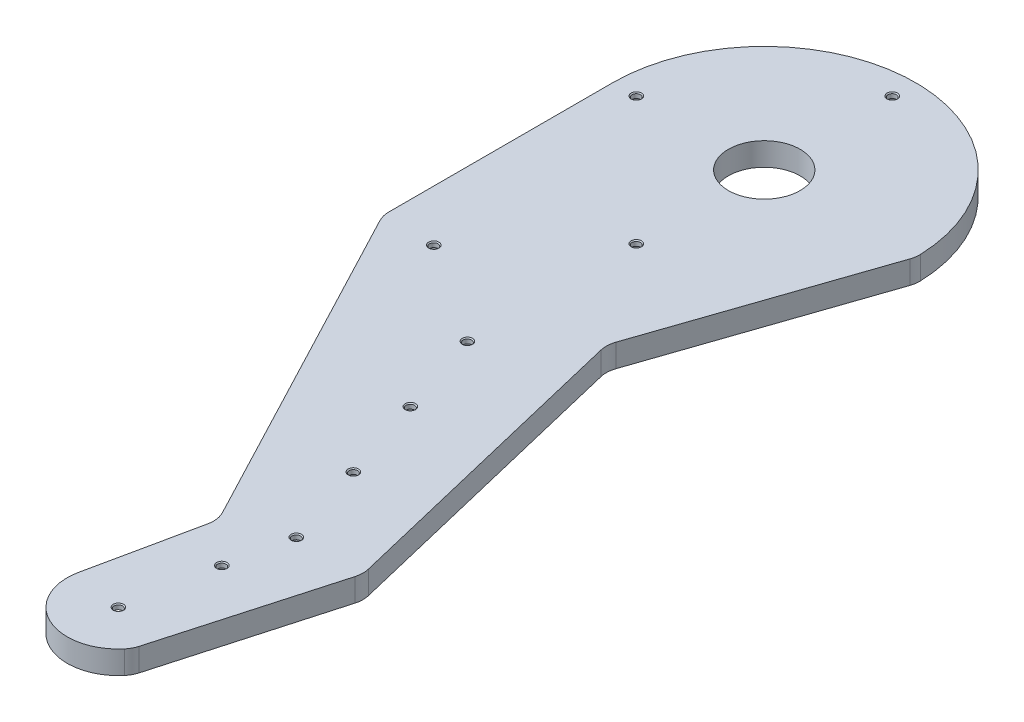
SolidWorks part; units mm, degrees
ref_plane "前视基准面" through (0, 0, 0) normal (0, 0, 1) x (1, 0, 0)
ref_plane "上视基准面" through (0, 0, 0) normal (0, 1, 0) x (1, 0, 0)
ref_plane "右视基准面" through (0, 0, 0) normal (1, 0, 0) x (0, 0, -1)
sketch "草图1" plane through (0, 0, 0) normal (0, 1, 0) x (1, 0, 0)
  line L1 (59.1175, 105.8237) -> (28.3621, 15.8237)
  line L2 (28.3621, 15.8237) -> (58.3577, -109.1763)
  line L3 (58.3577, -109.1763) -> (38.6011, -179.1763)
  line L4 (-59.1082, 15.8237) -> (11.7869, -119.1763)
  line L5 (-59.1175, 105.8237) -> (-59.1082, 15.8237)
  line L6 (11.7869, -119.1763) -> (2.2339, -164.1763)
  arc A0 (59.1175, 105.8237) -> (-59.1175, 105.8115) centre (0, 105.8237) ccw
  arc A1 (2.2339, -164.1763) -> (38.6011, -179.1763) centre (21.7979, -168.3296) ccw
  point P3 (0, 105.8237)
  dimension "D4" = 70
  dimension "D8" = 20
  dimension "D1" = 90
  dimension "D3" = 125
  dimension "D5" = 135
  dimension "D6" = 45
  dimension "D7" = 90
extrude "凸台-拉伸1" add sketch "草图1" along normal blind 5 contours L6 A1 L3 L2 L1 A0 L5 L4
sketch "草图5" plane through (0, 0, 0) normal (0, -1, 0) x (-1, 0, 0)
  circle A1 centre (-21.7979, -168.3296) radius 14
sketch "草图6" plane through (0, 5, 0) normal (0, 1, 0) x (1, 0, 0)
  circle A1 centre (0, 155.8237) radius 5
  circle A2 centre (0, 55.8237) radius 5
  circle A3 centre (-50, 105.8237) radius 5
  circle A4 centre (-39.1082, 15.8237) radius 5
  circle A5 centre (50, 105.8237) radius 5 [skipped]
  point P0 (0, 0)
  point P5 (0, 105.8237)
  dimension "D1" = 4
  dimension "D2" = 50
  dimension "D3" = 50
  dimension "D4" = 50
  dimension "D5" = 50
fillet "圆角1" radius 10 6 edges at (59.1175, 2.5, -105.8237) (38.6011, 2.5, 179.1763) (11.7869, 2.5, 119.1763) (58.3577, 2.5, 109.1763) (28.3621, 2.5, -15.8237) (-59.1082, 2.5, -15.8237)
sketch "草图7" plane through (0, 5, 0) normal (0, 1, 0) x (1, 0, 0)
  circle A0 centre (0, -10.1676) radius 5
  circle A2 centre (10.9623, -43.4066) radius 5
  circle A3 centre (21.9246, -76.6455) radius 5
  circle A4 centre (32.887, -109.8844) radius 5
  circle A5 centre (27.8629, -133.988) radius 5
  dimension "D2" = 10
  dimension "D1" = 4
sketch "草图8" plane through (0, 5, 0) normal (0, 1, 0) x (1, 0, 0)
  line L6 (29.3004, 18.5693) -> (58.5546, 104.1765)
  line L7 (-59.1175, 105.8237) -> (-59.1085, 18.2892)
  line L8 (-57.9619, 13.6408) -> (10.1089, -115.9809)
  line L9 (11.0374, -122.7069) -> (2.2339, -164.1763)
  line L10 (39.0813, -177.475) -> (57.6488, -111.6881)
  line L11 (57.7487, -106.6385) -> (29.0391, 13.0022)
  line L12 (29.3004, 18.5693) -> (58.5546, 104.1765)
  line L13 (-59.1175, 105.8237) -> (-59.1085, 18.2892)
  line L14 (-57.9619, 13.6408) -> (10.1089, -115.9809)
  line L15 (11.0374, -122.7069) -> (2.2339, -164.1763)
  line L16 (39.0813, -177.475) -> (57.6488, -111.6881)
  line L17 (57.7487, -106.6385) -> (29.0391, 13.0022)
  arc A8 (58.5546, 104.1765) -> (59.0866, 107.7331) centre (49.0919, 107.4101) ccw
  arc A9 (59.0866, 107.7331) -> (-59.1175, 105.8237) centre (0, 105.8237) ccw
  arc A10 (-59.1085, 18.2892) -> (-57.9619, 13.6408) centre (-49.1085, 18.2902) ccw
  arc A11 (11.0374, -122.7069) -> (10.1089, -115.9809) centre (1.2554, -120.6303) ccw
  arc A12 (2.2339, -164.1763) -> (37.1166, -181.1879) centre (21.7979, -168.3296) ccw
  arc A13 (37.1166, -181.1879) -> (39.0813, -177.475) centre (29.4573, -174.7587) ccw
  arc A14 (57.6488, -111.6881) -> (57.7487, -106.6385) centre (48.0248, -108.9719) ccw
  arc A15 (29.3004, 18.5693) -> (29.0391, 13.0022) centre (38.7631, 15.3356) ccw
  arc A16 (58.5546, 104.1765) -> (59.0866, 107.7331) centre (49.0919, 107.4101) ccw
  arc A17 (59.0866, 107.7331) -> (-59.1175, 105.8237) centre (0, 105.8237) ccw
  arc A18 (-59.1085, 18.2892) -> (-57.9619, 13.6408) centre (-49.1085, 18.2902) ccw
  arc A19 (11.0374, -122.7069) -> (10.1089, -115.9809) centre (1.2554, -120.6303) ccw
  arc A20 (2.2339, -164.1763) -> (37.1166, -181.1879) centre (21.7979, -168.3296) ccw
  arc A21 (37.1166, -181.1879) -> (39.0813, -177.475) centre (29.4573, -174.7587) ccw
  arc A22 (57.6488, -111.6881) -> (57.7487, -106.6385) centre (48.0248, -108.9719) ccw
  arc A23 (29.3004, 18.5693) -> (29.0391, 13.0022) centre (38.7631, 15.3356) ccw
  dimension "D1" = 0
extrude "凸台-拉伸2" add sketch "草图8" along normal blind 2
extrude "切除-拉伸2" cut sketch "草图7" against normal through all and the other way through all
extrude "切除-拉伸4" cut sketch "草图5" against normal blind 7 and the other way through all
sketch "草图9" plane through (0, 7, 0) normal (0, 1, 0) x (1, 0, 0)
  circle A2 centre (0, 105.8237) radius 14
extrude "切除-拉伸5" cut sketch "草图9" against normal blind 10
extrude "切除-拉伸7" cut sketch "草图6" against normal blind 10 and the other way blind 10
sketch "草图10" plane through (0, 7, 0) normal (0, 1, 0) x (1, 0, 0)
  line L6 (29.3004, 18.5693) -> (58.5546, 104.1765)
  line L7 (-59.1175, 105.8237) -> (-59.1085, 18.2892)
  line L8 (-57.9619, 13.6408) -> (10.1089, -115.9809)
  line L9 (11.0374, -122.7069) -> (2.2339, -164.1763)
  line L10 (39.0813, -177.475) -> (57.6488, -111.6881)
  line L11 (57.7487, -106.6385) -> (29.0391, 13.0022)
  line L12 (29.3004, 18.5693) -> (58.5546, 104.1765)
  line L13 (-59.1175, 105.8237) -> (-59.1085, 18.2892)
  line L14 (-57.9619, 13.6408) -> (10.1089, -115.9809)
  line L15 (11.0374, -122.7069) -> (2.2339, -164.1763)
  line L16 (39.0813, -177.475) -> (57.6488, -111.6881)
  line L17 (57.7487, -106.6385) -> (29.0391, 13.0022)
  circle A0 centre (0, 105.8237) radius 14
  arc A8 (29.3004, 18.5693) -> (29.0391, 13.0022) centre (38.7631, 15.3356) ccw
  arc A9 (58.5546, 104.1765) -> (59.0866, 107.7331) centre (49.0919, 107.4101) ccw
  arc A10 (59.0866, 107.7331) -> (-59.1175, 105.8237) centre (0, 105.8237) ccw
  arc A11 (-59.1085, 18.2892) -> (-57.9619, 13.6408) centre (-49.1085, 18.2902) ccw
  arc A12 (11.0374, -122.7069) -> (10.1089, -115.9809) centre (1.2554, -120.6303) ccw
  arc A13 (2.2339, -164.1763) -> (37.1166, -181.1879) centre (21.7979, -168.3296) ccw
  arc A14 (37.1166, -181.1879) -> (39.0813, -177.475) centre (29.4573, -174.7587) ccw
  arc A15 (57.6488, -111.6881) -> (57.7487, -106.6385) centre (48.0248, -108.9719) ccw
  arc A16 (29.3004, 18.5693) -> (29.0391, 13.0022) centre (38.7631, 15.3356) ccw
  arc A17 (58.5546, 104.1765) -> (59.0866, 107.7331) centre (49.0919, 107.4101) ccw
  arc A18 (59.0866, 107.7331) -> (-59.1175, 105.8237) centre (0, 105.8237) ccw
  arc A19 (-59.1085, 18.2892) -> (-57.9619, 13.6408) centre (-49.1085, 18.2902) ccw
  arc A20 (11.0374, -122.7069) -> (10.1089, -115.9809) centre (1.2554, -120.6303) ccw
  arc A21 (2.2339, -164.1763) -> (37.1166, -181.1879) centre (21.7979, -168.3296) ccw
  arc A22 (37.1166, -181.1879) -> (39.0813, -177.475) centre (29.4573, -174.7587) ccw
  arc A23 (57.6488, -111.6881) -> (57.7487, -106.6385) centre (48.0248, -108.9719) ccw
  dimension "D1" = 0
extrude "凸台-拉伸3" add sketch "草图10" along normal blind 2
sketch "草图11" plane through (0, 7, 0) normal (0, -1, 0) x (1, 0, 0)
  point P0 (0, -155.8237)
  point P1 (-50, -105.8237)
  point P3 (0, -55.8237)
  point P5 (-39.1082, -15.8237)
  point P7 (0, 10.1676)
  point P9 (10.9623, 43.4066)
  point P11 (21.9246, 76.6455)
  point P13 (32.887, 109.8844)
  point P15 (27.8629, 133.988)
sketch "草图12" plane through (0, 9, 0) normal (0, 1, 0) x (1, 0, 0)
  point P0 (0, 155.8237)
  point P1 (0, 55.8237)
  point P3 (-50, 105.8237)
  point P5 (-39.1082, 15.8237)
  point P7 (0, -10.1676)
  point P9 (10.9623, -43.4066)
  point P11 (21.9246, -76.6455)
  point P13 (32.887, -109.8844)
  point P15 (27.8629, -133.988)
hole_wizard "M4 螺纹孔1" positions "草图12" profile "草图13" tap size "M4" standard "GB" end condition up to next
sketch "草图13" plane through (0, 9, -155.8237) normal (1, 0, 0) x (0, 0, 1)
  line L0 (0, 0) -> (0, 2)
  line L1 (0, 2) -> (1.65, 2)
  line L2 (1.65, 2) -> (1.65, 0.375)
  line L3 (1.65, 0.375) -> (2.025, 0)
  line L5 (2.025, 0) -> (0, 0)
  line L6 (-1.65, 0.375) -> (-2.025, 0) construction
  line L11 (0, -6.35) -> (0, 107.95) construction
  dimension "通孔螺纹孔钻头直径" = 3.3
  dimension "通孔螺纹孔钻头深度" = 2
  dimension "近端锥形沉头孔直径" = 4.05
  dimension "近端锥形沉头孔角度" = 90
cosmetic thread "孔螺纹线1" parameters "D2"=4
cosmetic thread "孔螺纹线2" parameters "D2"=4
cosmetic thread "孔螺纹线3" parameters "D2"=4
cosmetic thread "孔螺纹线4" parameters "D2"=4
cosmetic thread "孔螺纹线5" parameters "D2"=4
cosmetic thread "孔螺纹线6" parameters "D2"=4
cosmetic thread "孔螺纹线7" parameters "D2"=4
cosmetic thread "孔螺纹线8" parameters "D2"=4
cosmetic thread "孔螺纹线9" parameters "D2"=4
sketch "草图14" plane through (0, 9, 0) normal (0, 1, 0) x (1, 0, 0)
  point P0 (21.7979, -168.3296)
sketch "草图15" plane through (0, 9, 0) normal (0, 1, 0) x (1, 0, 0)
  point P0 (21.7979, -168.3296)
hole_wizard "M4 螺纹孔2" positions "草图15" profile "草图16" tap size "M4" standard "DIN"
sketch "草图16" plane through (21.7979, 9, 168.3296) normal (1, 0, 0) x (0, 0, 1)
  line L0 (0, 0) -> (0, 11.0914)
  line L1 (0, 11.0914) -> (1.65, 10.1)
  line L2 (1.65, 10.1) -> (1.65, 0.375)
  line L3 (1.65, 0.375) -> (2.025, 0)
  line L5 (2.025, 0) -> (0, 0)
  line L6 (-1.65, 0.375) -> (-2.025, 0) construction
  line L10 (0, 11.0914) -> (-1.65, 10.1) construction
  line L11 (0, -6.35) -> (0, 107.95) construction
  dimension "螺纹孔钻头直径" = 3.3
  dimension "螺纹孔钻头深度" = 10.1
  dimension "近端锥形沉头孔直径" = 4.05
  dimension "近端锥形沉头孔角度" = 90
  dimension "导头角度" = 118
cosmetic thread "孔螺纹线10" parameters "D1"=8, "D2"=4
